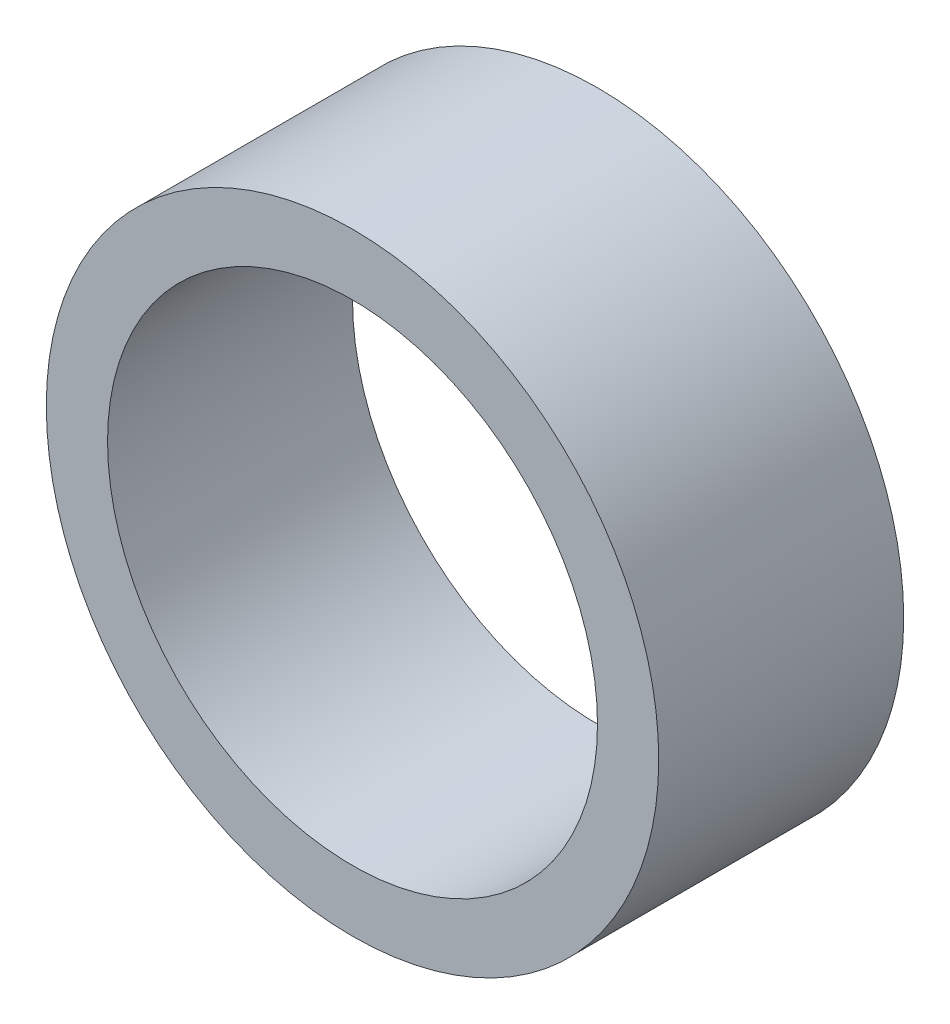
SolidWorks part; units mm, degrees
material "Nylon 101"
ref_plane "Front Plane" through (0, 0, 0) normal (0, 0, 1) x (1, 0, 0)
ref_plane "Top Plane" through (0, 0, 0) normal (0, 1, 0) x (1, 0, 0)
ref_plane "Right Plane" through (0, 0, 0) normal (1, 0, 0) x (0, 0, -1)
sketch "Sketch1" plane through (0, 0, 0) normal (0, 0, 1) x (1, 0, 0)
  circle A0 centre (0, 0) radius 7.9375
  circle A1 centre (0, 0) radius 6.35
  dimension "D1" = 15.875
  dimension "D2" = 12.7
extrude "Boss-Extrude1" add sketch "Sketch1" along normal blind 6.35
